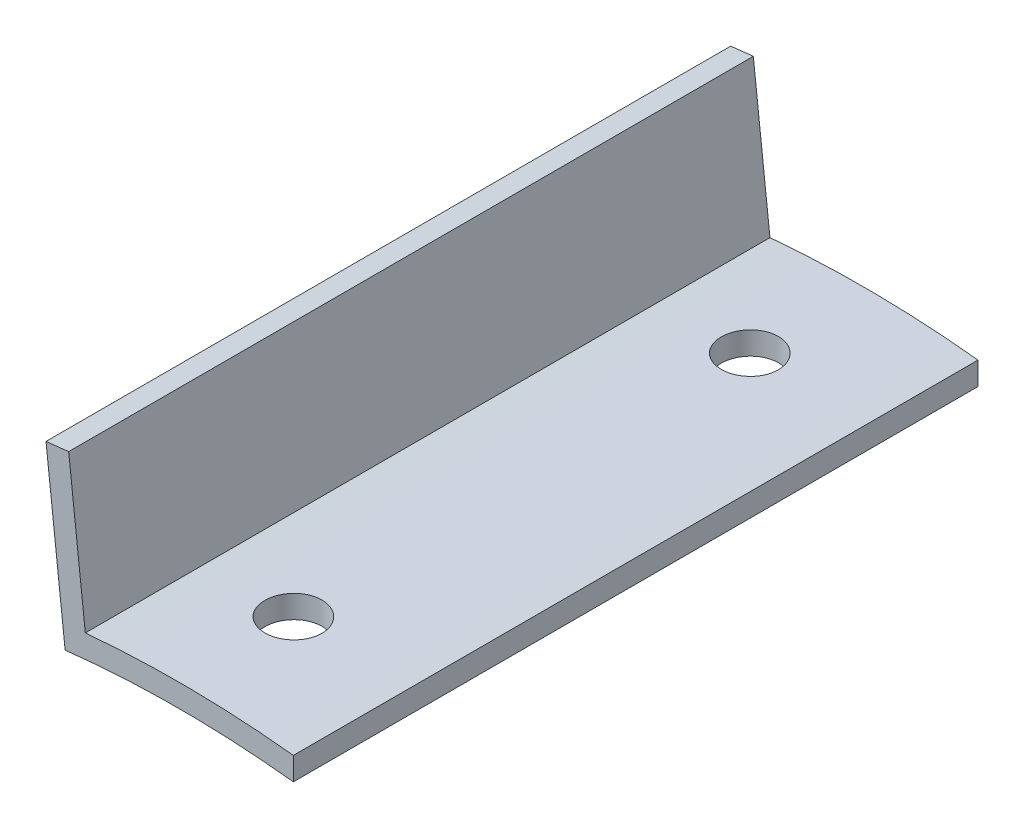
SolidWorks part; units mm, degrees
ref_plane "Front Plane" through (0, 0, 0) normal (0, 0, 1) x (1, 0, 0)
ref_plane "Top Plane" through (0, 0, 0) normal (0, 1, 0) x (1, 0, 0)
ref_plane "Right Plane" through (0, 0, 0) normal (1, 0, 0) x (0, 0, -1)
sketch "Sketch1" plane through (0, 0, 0) normal (0, 0, 1) x (1, 0, 0)
  line L4 (-12.7, 113.5923) -> (-14.8299, 132.6423)
  line L5 (-14.8299, 132.6423) -> (-12.3056, 132.9245)
  line L6 (-12.3056, 132.9245) -> (-10.4549, 116.3713)
  line L7 (0, 0) -> (0, 251.8364) construction
  line L8 (12.7, 113.5923) -> (12.7, 116.1477)
  circle A3 centre (0, 0) radius 114.3 construction
  arc A4 (12.7, 113.5923) -> (-12.7, 113.5923) centre (0, 0) ccw
  arc A5 (-10.4549, 116.3713) -> (12.7, 116.1477) centre (0, 0) cw
  dimension "D1" = 228.6
  dimension "D5" = 2.54
  dimension "D4" = 25.4
  dimension "D2" = 19.05
  dimension "D3" = 2.54
extrude "Boss-Extrude1" add sketch "Sketch1" along normal blind 76.2
sketch "Sketch2" plane through (0, 0, 0) normal (0, 1, 0) x (1, 0, 0)
  line L0 (0, 0) -> (0, -76.2) construction
  line L1 (12.7, 0) -> (-10.4549, 0) construction
  line L3 (-10.4549, -76.2) -> (12.7, -76.2) construction
  line L4 (12.7, -38.1) -> (-94.2263, -38.1) construction
  line L5 (12.7, -76.2) -> (12.7, 0) construction
  circle A2 centre (0, -12.7) radius 3.175
  circle A3 centre (0, -63.5) radius 3.175
  dimension "D2" = 12.7
  dimension "D1" = 6.35
  dimension "D3" = 12.7
extrude "Cut-Extrude1" cut sketch "Sketch2" along normal through all
